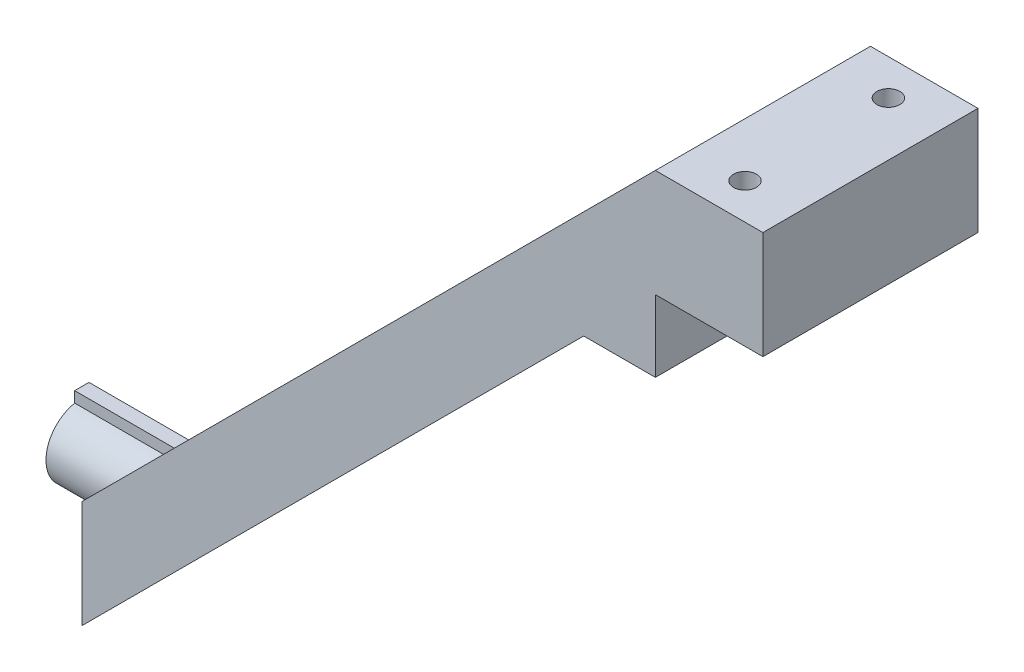
SolidWorks part; units mm, degrees
ref_plane "Front Plane" through (0, 0, 0) normal (0, 0, 1) x (1, 0, 0)
ref_plane "Top Plane" through (0, 0, 0) normal (0, 1, 0) x (1, 0, 0)
ref_plane "Right Plane" through (0, 0, 0) normal (1, 0, 0) x (0, 0, -1)
sketch "Sketch1" plane through (0, 0, 0) normal (0, 0, 1) x (1, 0, 0)
  line L0 (0, 0) -> (15, 0)
  line L1 (15, 0) -> (15, -15)
  line L2 (15, -15) -> (0, -15)
  line L3 (0, 0) -> (-80, -80)
  line L4 (-10, -25) -> (-80, -95)
  line L5 (-80, -80) -> (-80, -95)
  line L6 (0, 0) -> (0, -15) construction
  line L7 (0, -15) -> (0, -25)
  line L8 (0, -25) -> (-10, -25)
  line L9 (0, -15) -> (-10, -25) construction
  point P6 (7.5, 0)
  dimension "D1" = 80
  dimension "D2" = 45
  dimension "D3" = 15
  dimension "D4" = 15
  dimension "D5" = 7.5
  dimension "D6" = 10
extrude "Boss-Extrude1" add sketch "Sketch1" along normal blind 30
sketch "Sketch2" plane through (0, 0, 0) normal (0, 1, 0) x (1, 0, 0)
  line L0 (7.5, 0) -> (7.5, -30) construction
  line L1 (7.5, -15) -> (15, -15) construction
  line L4 (15, 0) -> (0, 0)
  line L5 (0, 0) -> (0, -30)
  line L6 (0, -30) -> (15, -30)
  line L7 (15, -30) -> (15, 0)
  line L8 (15, 0) -> (0, 0) construction
  line L9 (0, 0) -> (0, -30) construction
  line L10 (0, -30) -> (15, -30) construction
  line L11 (15, -30) -> (15, 0) construction
  circle A0 centre (7.5, -5) radius 1.6
  circle A1 centre (7.5, -25) radius 1.6
  point P1 (7.5, -25)
  point P8 (7.5, -5)
  point P12 (7.5, -15)
  dimension "D3" = 3.2
  dimension "D2" = 20
  dimension "D1" = 0
extrude "Cut-Extrude1" cut sketch "Sketch2" against normal up to surface (15 mm away) and the other way through all up to face at (7.5, -15, 15)
sketch "Sketch3" plane through (-80, 0, 0) normal (-1, 0, 0) x (0, 0, 1)
  line L0 (0, -87.5) -> (30, -87.5) construction
  line L1 (15, -80) -> (15, -95) construction
  line L2 (16, -83.899) -> (16, -82.601) construction
  line L3 (14, -83.899) -> (15, -83.899) construction
  line L4 (0, -80) -> (0, -95)
  line L5 (0, -95) -> (30, -95)
  line L6 (30, -95) -> (30, -80)
  line L7 (30, -80) -> (0, -80)
  line L8 (0, -80) -> (0, -95) construction
  line L9 (0, -95) -> (30, -95) construction
  line L10 (30, -95) -> (30, -80) construction
  line L11 (30, -80) -> (0, -80) construction
  line L12 (14, -82.601) -> (14, -81.101)
  line L13 (14, -81.101) -> (16, -81.101)
  line L14 (16, -82.601) -> (16, -81.101)
  line L15 (14, -83.899) -> (16, -81.101) construction
  line L16 (14, -81.101) -> (16, -83.899) construction
  line L17 (15, -83.899) -> (16, -83.899) construction
  line L18 (14, -83.899) -> (14, -82.601) construction
  arc A0 (14, -82.601) -> (16, -82.601) centre (15, -87.5) ccw
  point P12 (15, -82.5)
  dimension "D2" = 10
  dimension "D3" = 1.5
  dimension "D4" = 2
  dimension "D1" = 0
extrude "Boss-Extrude2" add sketch "Sketch3" along normal blind 15
